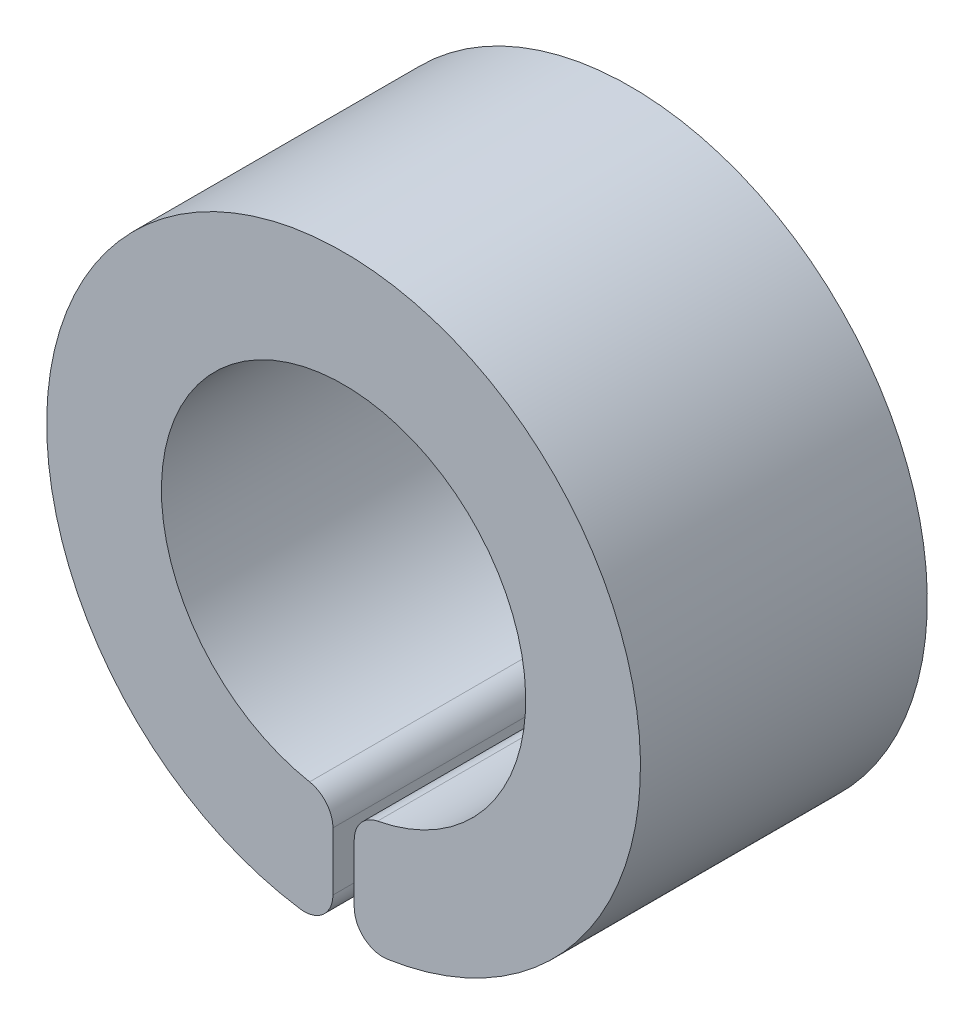
SolidWorks part; units mm, degrees
ref_plane "Front Plane" through (0, 0, 0) normal (0, 0, 1) x (1, 0, 0)
ref_plane "Top Plane" through (0, 0, 0) normal (0, 1, 0) x (1, 0, 0)
ref_plane "Right Plane" through (0, 0, 0) normal (1, 0, 0) x (0, 0, -1)
sketch "Sketch1" plane through (0, 0, 0) normal (0, 0, 1) x (1, 0, 0)
  circle A0 centre (0, 0) radius 3.175
  circle A1 centre (0, 0) radius 5.175
  dimension "D1" = 6.35
  dimension "D2" = 2
extrude "Boss-Extrude1" add sketch "Sketch1" along normal blind 5
sketch "Sketch2" plane through (0, 0, 0) normal (1, 0, 0) x (0, 0, -1)
  line L0 (2.75, 0) -> (-2.75, 0) construction
  point P0 (-2.5, 0)
sketch "Sketch5" plane through (0, 0, 0) normal (0, 1, 0) x (1, 0, 0)
  line L0 (-5.175, -5) -> (5.175, -5) construction
  line L1 (0.1856, 0) -> (-0.1856, 0)
  line L2 (0.1856, 0) -> (0.1856, -5)
  line L3 (0.1856, -5) -> (-0.1856, -5)
  line L4 (-0.1856, 0) -> (-0.1856, -5)
  line L5 (0.1856, 0) -> (-0.1856, -5) construction
  line L6 (0.1856, -5) -> (-0.1856, 0) construction
  point P0 (0, -2.5)
extrude "Cut-Extrude1" cut sketch "Sketch5" against normal blind 20
fillet "Fillet1" radius 0.5 4 edges at (0.1856, -5.1717, 2.5) (0.1856, -3.1696, 2.5) (-0.1856, -5.1717, 2.5) (-0.1856, -3.1696, 2.5)
hole_wizard "Tap Drill for M3x0.5 Tap2" positions "3DSketch2" profile "Sketch4" hole size "M3x0.5" standard "ANSI Metric"
sketch3d "3DSketch2"
  point P0 (0, 0, 2.5)
  point P3 (2.2922, 4.6396, 2.5)
sketch "Sketch4" plane through (2.2922, 4.6396, 2.5) normal (0, 0, 1) x (-0.8965, 0.4429, 0)
  line L0 (0, 0) -> (0, 5)
  line L1 (0, 5) -> (1.25, 4.2489)
  line L2 (1.25, 4.2489) -> (1.25, 0)
  line L5 (1.25, 0) -> (0, 0)
  line L10 (0, 5) -> (-1.25, 4.2489) construction
  line L11 (0, -6.35) -> (0, 107.95) construction
  dimension "Hole Dia." = 2.5
  dimension "Hole Depth" = 5
  dimension "Drill Angle" = 118
